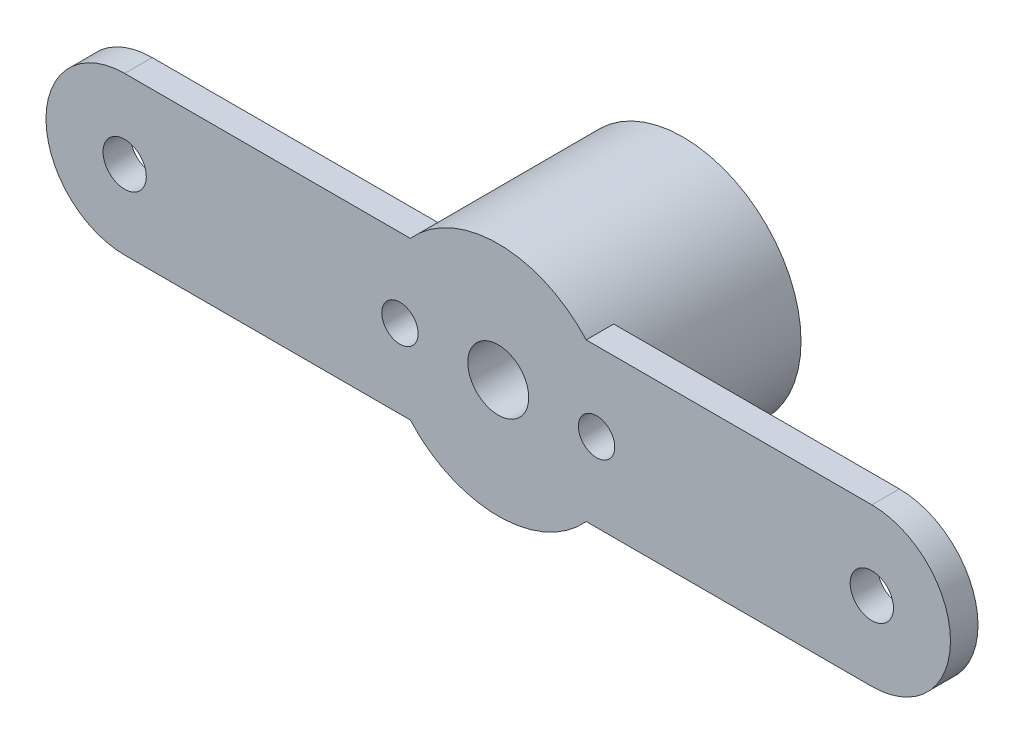
SolidWorks part; units mm, degrees
ref_plane "前视基准面" through (0, 0, 0) normal (0, 0, 1) x (1, 0, 0)
ref_plane "上视基准面" through (0, 0, 0) normal (0, 1, 0) x (1, 0, 0)
ref_plane "右视基准面" through (0, 0, 0) normal (1, 0, 0) x (0, 0, -1)
sketch "草图1" plane through (0, 0, 0) normal (0, 0, 1) x (1, 0, 0)
  line L0 (4.4721, 4) -> (19, 4)
  line L1 (-19, -4) -> (-4.4721, -4)
  line L2 (4.4721, -4) -> (19, -4)
  line L3 (-19, 4) -> (-4.4721, 4)
  circle A0 centre (0, 0) radius 1.55
  circle A1 centre (19, 0) radius 1.1
  circle A2 centre (-19, 0) radius 1.1
  arc A3 (-19, 4) -> (-19, -4) centre (-19, 0) ccw
  arc A4 (19, -4) -> (19, 4) centre (19, 0) ccw
  arc A5 (-4.4721, -4) -> (4.4721, -4) centre (0, 0) ccw
  arc A6 (4.4721, 4) -> (-4.4721, 4) centre (0, 0) ccw
  circle A7 centre (-5, 0) radius 0.925
  circle A8 centre (5, 0) radius 0.925
  dimension "D3" = 2.2
  dimension "D4" = 2.2
  dimension "D5" = 3.1
  dimension "D8" = 12
  dimension "D7" = 8
  dimension "D9" = 4
  dimension "D6" = 8
  dimension "D11" = 1.85
  dimension "D12" = 1.85
  dimension "D1" = 19
  dimension "D2" = 19
  dimension "D10" = 4
  dimension "D13" = 5
  dimension "D14" = 5
extrude "凸台-拉伸1" add sketch "草图1" along normal blind 1.4
sketch "草图2" plane through (0, 0, 0) normal (0, 0, -1) x (-1, 0, 0)
  circle A0 centre (0, 0) radius 6
  circle A1 centre (0, 0) radius 1.55
  circle A2 centre (-5, 0) radius 0.925
  circle A3 centre (5, 0) radius 0.925
  dimension "D1" = 3.1
extrude "凸台-拉伸2" add sketch "草图2" along normal blind 8
